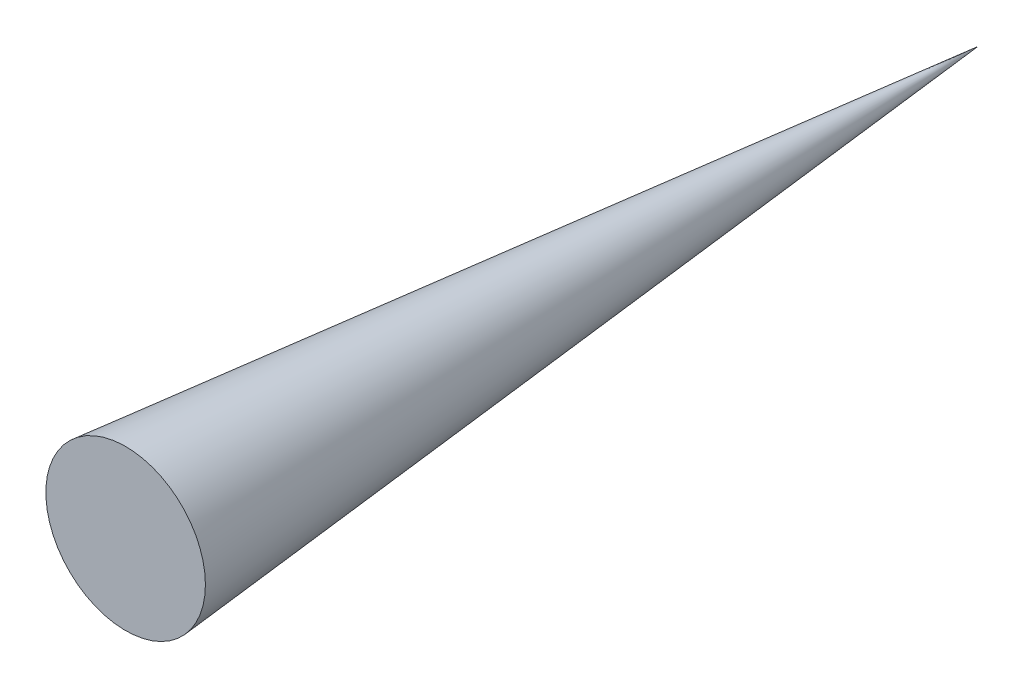
SolidWorks part; units mm, degrees
ref_plane "Front" through (0, 0, 0) normal (0, 0, 1) x (1, 0, 0)
ref_plane "Top" through (0, 0, 0) normal (0, 1, 0) x (1, 0, 0)
ref_plane "Right" through (0, 0, 0) normal (1, 0, 0) x (0, 0, -1)
sketch "Sketch1" plane through (0, 0, 0) normal (0, 1, 0) x (1, 0, 0)
  line L0 (0, 0) -> (-30, 0)
  line L1 (0, 0) -> (0, 320.5)
  line L2 (0, 320.5) -> (-30, 0)
  line L3 (0, -33.993) -> (0, 333.1348) construction
  dimension "D1" = 30
  dimension "D2" = 320.5
revolve "Revolve1" add sketch "Sketch1" angle 360 about L3
